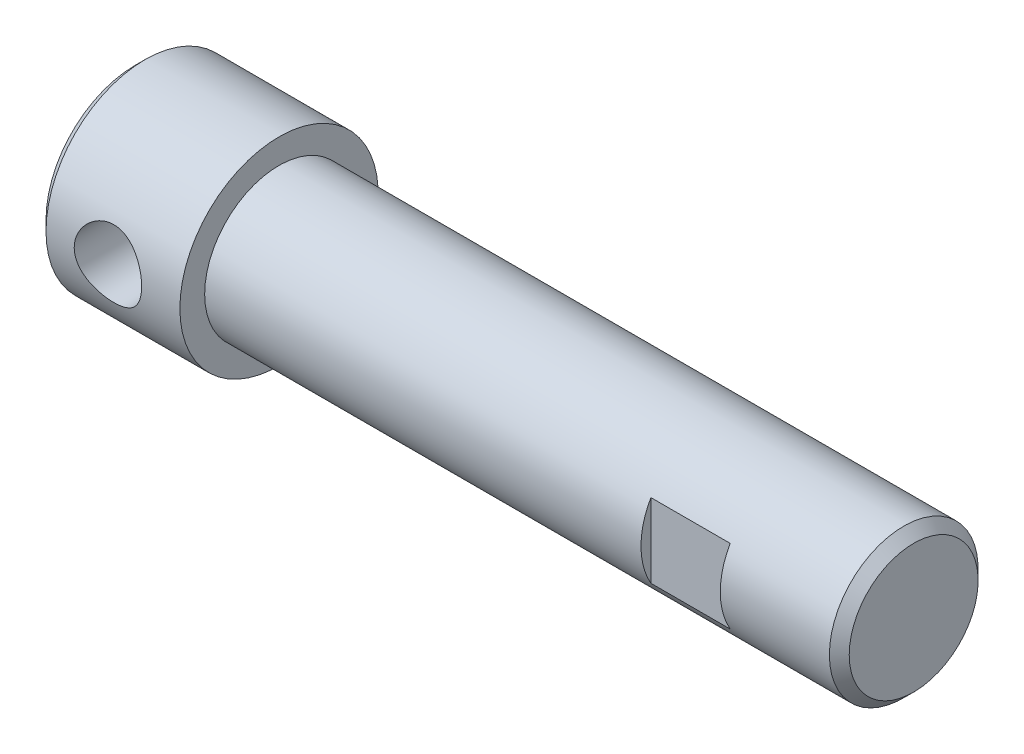
SolidWorks part; units mm, degrees
ref_plane "Plan de face" through (0, 0, 0) normal (0, 0, 1) x (1, 0, 0)
ref_plane "Plan de dessus" through (0, 0, 0) normal (0, 1, 0) x (1, 0, 0)
ref_plane "Plan de droite" through (0, 0, 0) normal (1, 0, 0) x (0, 0, -1)
sketch "Esquisse1" plane through (0, 0, 0) normal (0, 0, 1) x (1, 0, 0)
  line L0 (-22.2027, 0) -> (72.6886, 0) construction
  line L1 (36.1035, 0) -> (-36.1035, 0) construction
  line L2 (-14.5, 4) -> (-14.5, 10)
  line L3 (-14.5, 10) -> (0, 10)
  line L4 (0, -55) -> (0, 55) construction
  line L5 (0, 10) -> (0, 7.5)
  line L6 (0, 7.5) -> (64, 7.5)
  line L7 (64, 7.5) -> (64, 0)
  line L8 (-14.5, 4) -> (2, 4)
  line L9 (2, 4) -> (2, 3.75)
  line L10 (2, 3.75) -> (4, 3.75)
  line L11 (4, 3.75) -> (6.1651, 0)
  line L12 (64, 0) -> (6.1651, 0)
  dimension "D1" = 8
  dimension "D2" = 20
  dimension "D3" = 15
  dimension "D4" = 7.5
  dimension "D5" = 14.5
  dimension "D6" = 64
  dimension "D7" = 16.5
  dimension "D8" = 2
  dimension "D9" = 60
revolve "Révolution1" add sketch "Esquisse1" angle 360 about L0
chamfer "Chanfrein1" distance 1 angle 45 2 edges at (64, 0, 7.5) (-14.5, 0, 10)
hole_wizard "Trou taraudé M81" positions "Esquisse3D2" profile "Esquisse3" tap size "M8" standard "ISO"
sketch3d "Esquisse3D2"
  point P0 (-7.2554, 0, 10)
sketch "Esquisse3" plane through (-7.2554, 0, 10) normal (1, 0, 0) x (0, -1, 0)
  line L0 (0, 0) -> (0, 6)
  line L1 (0, 6) -> (3.4, 6)
  line L2 (3.4, 6) -> (3.4, 0)
  line L5 (3.4, 0) -> (0, 0)
  line L11 (0, -6.35) -> (0, 107.95) construction
  dimension "Diamètre du trou pour taraudage jusqu'au prochain" = 6.8
  dimension "Profondeur du trou pour taraudage jusqu'au prochain" = 6
cosmetic thread "Filetage de perçage1" parameters "D2"=8
sketch "Esquisse4" plane through (0, 0, 0) normal (0, 1, 0) x (1, 0, 0)
  line L0 (64, -6.5) -> (64, 6.5) construction
  line L1 (44, -9.3324) -> (52, -9.3324)
  line L2 (44, -9.3324) -> (44, -6.5)
  line L3 (44, -6.5) -> (52, -6.5)
  line L4 (52, -9.3324) -> (52, -6.5)
  line L6 (0, -7.5) -> (63, -7.5) construction
  dimension "D1" = 20
  dimension "D2" = 8
  dimension "D3" = 1
extrude "Enlèv. mat.-Extru.1" cut sketch "Esquisse4" against normal through all and the other way through all
